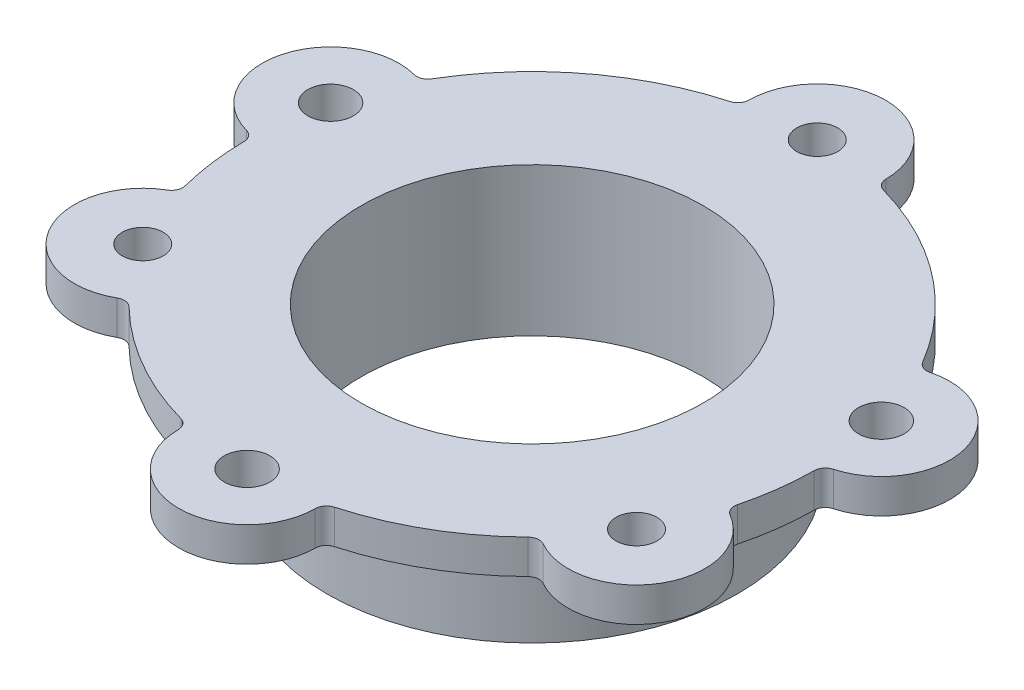
SolidWorks part; units mm, degrees
material "Delrin 2700 NC010, Low Viscosity Acetal Copolymer (SS)"
ref_plane "Front" through (0, 0, 0) normal (0, 0, 1) x (1, 0, 0)
ref_plane "Top" through (0, 0, 0) normal (0, 1, 0) x (1, 0, 0)
ref_plane "Right" through (0, 0, 0) normal (1, 0, 0) x (0, 0, -1)
sketch "Sketch1" plane through (0, 0, 0) normal (0, 1, 0) x (1, 0, 0)
  line L0 (-3, 0) -> (3, 0) construction
  line L5 (0, 0) -> (0, -12.5) construction
  line L8 (3, 0) -> (3, -12.5)
  line L9 (-3, 0) -> (-3, -12.5)
  line L12 (0, 0) -> (0, 12.5) construction
  line L15 (3, 0) -> (3, 12.5)
  line L18 (-3, 0) -> (-3, 12.5)
  line L21 (-1.5, -2.5981) -> (9.3253, -8.8481)
  line L24 (1.5, 2.5981) -> (12.3253, -3.6519)
  line L25 (0, 0) -> (10.8253, -6.25) construction
  line L26 (-1.5, 2.5981) -> (-12.3253, -3.6519)
  line L27 (1.5, -2.5981) -> (-9.3253, -8.8481)
  line L28 (0, 0) -> (-10.8253, -6.25) construction
  line L35 (0, 0) -> (-12.0741, 3.2352) construction
  line L36 (-0.7765, -2.8978) -> (-12.8505, 0.3375)
  line L37 (0.7765, 2.8978) -> (-11.2976, 6.133)
  line L38 (0, 25.1874) -> (0, -25.1874) construction
  line L39 (0, 0) -> (12.0741, 3.2352) construction
  line L40 (0.7765, -2.8978) -> (12.8505, 0.3375)
  line L41 (-0.7765, 2.8978) -> (11.2976, 6.133)
  circle A1 centre (0, 0) radius 7.5
  arc A11 (3, 0) -> (-3, 0) centre (0, 0) ccw
  arc A12 (-3, -12.5) -> (3, -12.5) centre (0, -12.5) ccw
  circle A13 centre (0, -12.5) radius 1
  circle A21 centre (0, 0) radius 12.5
  arc A22 (3, 0) -> (-3, 0) centre (0, 0) cw
  arc A23 (-3, 12.5) -> (3, 12.5) centre (0, 12.5) cw
  circle A24 centre (0, 12.5) radius 0.9
  arc A25 (12.3253, -3.6519) -> (9.3253, -8.8481) centre (10.8253, -6.25) cw
  arc A26 (-1.5, -2.5981) -> (1.5, 2.5981) centre (0, 0) cw
  circle A27 centre (10.8253, -6.25) radius 0.9
  arc A28 (-9.3253, -8.8481) -> (-12.3253, -3.6519) centre (-10.8253, -6.25) cw
  arc A29 (-1.5, 2.5981) -> (1.5, -2.5981) centre (0, 0) cw
  circle A30 centre (-10.8253, -6.25) radius 0.9
  arc A31 (-0.7765, -2.8978) -> (0.7765, 2.8978) centre (0, 0) ccw
  arc A32 (-11.2976, 6.133) -> (-12.8505, 0.3375) centre (-12.0741, 3.2352) ccw
  circle A33 centre (-12.0741, 3.2352) radius 1
  circle A35 centre (12.0741, 3.2352) radius 1
  arc A36 (0.7765, -2.8978) -> (-0.7765, 2.8978) centre (0, 0) cw
  arc A37 (11.2976, 6.133) -> (12.8505, 0.3375) centre (12.0741, 3.2352) cw
  point P7 (0, 6.25)
  point P10 (0, -6.25)
  point P20 (-6.037, 1.6176)
  point P25 (-5.4127, -3.125)
  point P27 (5.4127, -3.125)
  point P30 (0, -15.5)
  point P37 (-5.4127, -3.125)
  point P38 (-5.4127, 3.125)
  point P52 (0, 0)
  point P55 (6.037, 1.6176)
  point P71 (-5.4127, -3.125)
  point P78 (-5.4127, 3.125)
  dimension "D2" = 15
  dimension "D6" = 3
  dimension "D7" = 2
  dimension "D5" = 25
  dimension "D1" = 1.8
  dimension "D4" = 2
  dimension "D8" = 12.5
  dimension "D3" = 75
extrude "Boss-Extrude1" add sketch "Sketch1" along normal blind 1.5 contours A24 A21 L15 A23 L18 | A24 A21 L18 A1 L15 | L41 A21 L15 A1 | A21 A35 L41 A1 L24 L40 | A37 L41 A21 A35 L40 | L24 A21 L40 | A1 L40 L24 | A27 A21 L24 L40 A1 L21 | A27 A21 L21 A25 L24 | L8 A21 L21 A1 | A13 A21 L8 A1 L9 | A21 A13 L9 A12 L8 | L27 A21 L9 A1 | A30 A21 L27 A1 L36 L26 | A30 A21 L26 A28 L27 | A1 L26 L36 | L36 A21 L26 | A33 A21 L36 L26 A1 L37 | A33 A21 L37 A32 L36 | L18 A21 L37 A1
fillet "Fillet1" radius 0.5 12 edges at (-3, 0.75, 12.1347) (3, 0.75, 12.1347) (9.0089, 0.75, 8.6654) (12.0089, 0.75, 3.4693) (12.4976, 0.75, -0.2429) (10.9447, 0.75, -6.0385) (3, 0.75, -12.1347) (-3, 0.75, -12.1347) (-10.9447, 0.75, -6.0385) (-12.4976, 0.75, -0.2429) (-12.0089, 0.75, 3.4693) (-9.0089, 0.75, 8.6654)
sketch "Sketch2" plane through (0, 0, 0) normal (0, -1, 0) x (1, 0, 0)
  circle A0 centre (0, 0) radius 9
  circle A1 centre (0, 0) radius 7.5 construction
  circle A2 centre (0, 0) radius 7.5
  dimension "D1" = 18
extrude "Boss-Extrude2" add sketch "Sketch2" along normal blind 5
equation "\"PostAngle\"=75"
equation "\"D3@Sketch1\"=\"PostAngle\""
